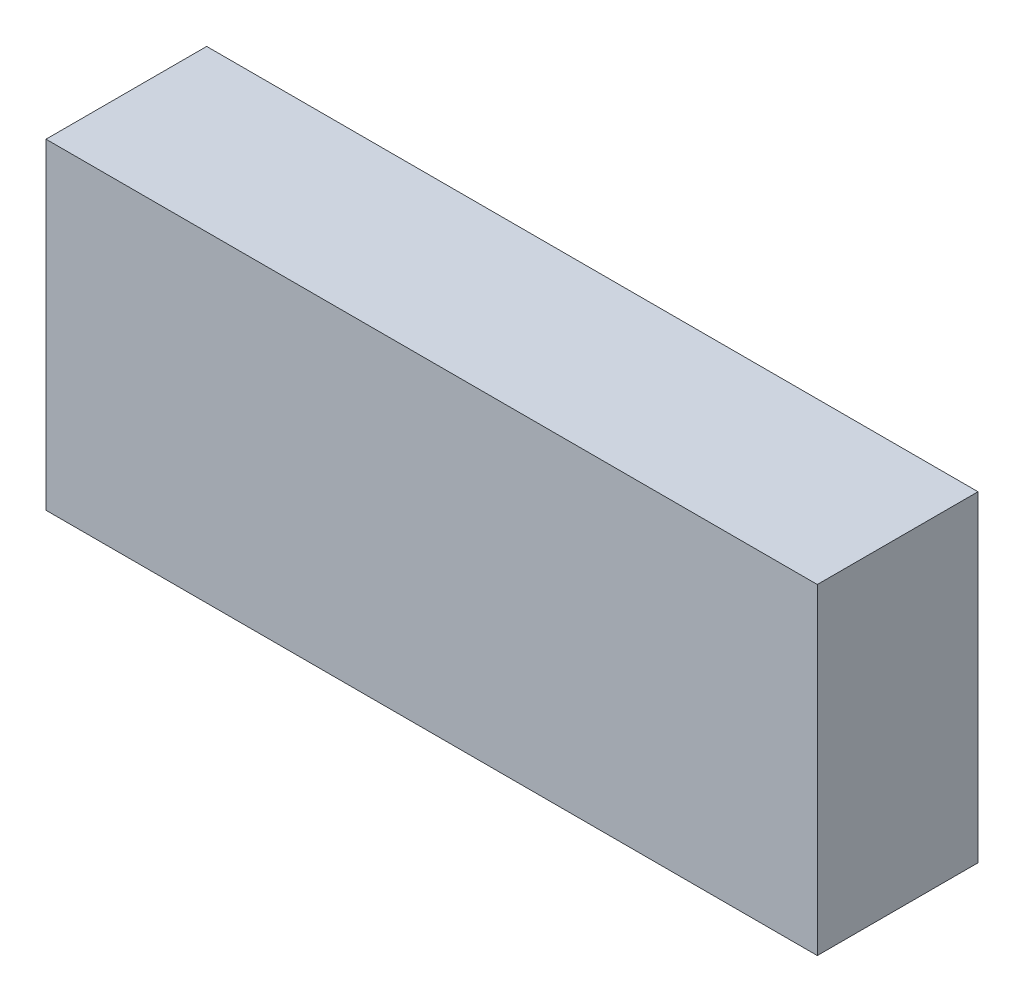
SolidWorks part; units mm, degrees
ref_plane "Front Plane" through (0, 0, 0) normal (0, 0, 1) x (1, 0, 0)
ref_plane "Top Plane" through (0, 0, 0) normal (0, 1, 0) x (1, 0, 0)
ref_plane "Right Plane" through (0, 0, 0) normal (1, 0, 0) x (0, 0, -1)
sketch "Sketch1" plane through (0, 0, 0) normal (0, 0, 1) x (1, 0, 0)
  line L1 (0, 0) -> (300, 0)
  line L2 (0, 0) -> (0, -125)
  line L3 (0, -125) -> (300, -125)
  line L4 (300, 0) -> (300, -125)
  dimension "D1" = 125
  dimension "D2" = 300
  dimension "D3" = 0
  dimension "D4" = 0
extrude "Boss-Extrude1" add sketch "Sketch1" along normal blind 62.5
